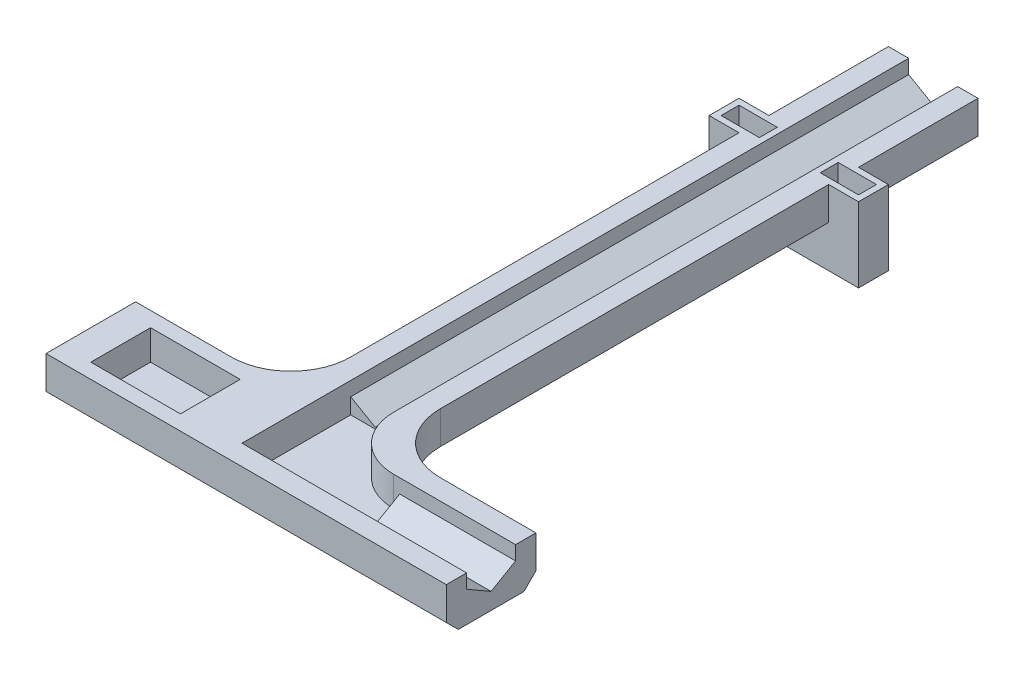
SolidWorks part; units mm, degrees
ref_plane "Front Plane" through (0, 0, 0) normal (0, 0, 1) x (1, 0, 0)
ref_plane "Top Plane" through (0, 0, 0) normal (0, 1, 0) x (1, 0, 0)
ref_plane "Right Plane" through (0, 0, 0) normal (1, 0, 0) x (0, 0, -1)
sketch "Sketch1" plane through (0, 0, 0) normal (0, 1, 0) x (1, 0, 0)
  line L0 (0, 0) -> (0, 15)
  line L1 (0, 15) -> (16, 15)
  line L2 (41, 25) -> (41, 115)
  line L3 (41, 115) -> (26, 115)
  line L4 (26, 115) -> (26, 25)
  line L5 (51, 15) -> (67, 15)
  line L6 (67, 15) -> (67, 0)
  line L7 (67, 0) -> (0, 0)
  arc A0 (26, 25) -> (16, 15) centre (16, 25) cw
  arc A1 (51, 15) -> (41, 25) centre (51, 25) cw
  point P10 (33.5, 115)
  point P11 (33.5, 0)
  point P16 (41, 15)
  dimension "D5" = 10
  dimension "D1" = 15
  dimension "D2" = 67
  dimension "D3" = 100
  dimension "D4" = 15
extrude "Boss-Extrude1" add sketch "Sketch1" along normal blind 7.5 contours L3 L4 L1 L2 | L7 L6 L5 L1 L0
sketch "Sketch2" plane through (0, 7.5, 0) normal (0, 1, 0) x (1, 0, 0)
  line L0 (33.5, 115) -> (33.5, 7.5)
  line L1 (41, 115) -> (26, 115) construction
  line L2 (33.5, 7.5) -> (67, 7.5)
  line L3 (67, 15) -> (67, 0) construction
  point P8 (67, 7.5)
sketch "Sketch3" plane through (0, 0, -115) normal (0, 0, -1) x (-1, 0, 0)
  line L0 (-41, 7.5) -> (-26, 7.5) construction
  line L1 (-37.6, 5.1329) -> (-33.5, 2.7657)
  line L2 (-33.5, 2.7657) -> (-29.4, 5.1329)
  line L3 (-29.4, 5.1329) -> (-29.4, 9.8671)
  line L4 (-29.4, 9.8671) -> (-33.5, 12.2343)
  line L5 (-33.5, 12.2343) -> (-37.6, 9.8671)
  line L6 (-37.6, 9.8671) -> (-37.6, 5.1329)
  circle A0 centre (-33.5, 7.5) radius 4.1 construction
  dimension "D1" = 8.2
sweep "Cut-Sweep1" cut profiles "Sketch3" path "Sketch2"
sketch "Sketch7" plane through (0, 7.5, 0) normal (0, 1, 0) x (1, 0, 0)
  line L5 (47.6, 11.6) -> (47.6, 3.4)
  line L6 (67, 3.4) -> (29.4, 3.4) construction
  line L7 (47.6, 3.4) -> (29.4, 3.4)
  line L8 (29.4, 3.4) -> (29.4, 21.6)
  line L14 (37.6, 115) -> (37.6, 11.6) construction
  line L19 (29.4, 21.6) -> (37.6, 21.6)
  line L20 (29.4, 115) -> (29.4, 3.4) construction
  line L21 (37.6, 115) -> (37.6, 11.6) construction
  line L22 (37.6, 21.6) -> (37.6, 20.6)
  line L23 (46.6, 11.6) -> (47.6, 11.6)
  line L24 (37.6, 11.6) -> (67, 11.6) construction
  arc A0 (37.6, 20.6) -> (46.6, 11.6) centre (46.6, 20.6) ccw
  point P16 (37.6, 11.6)
  dimension "D3" = 9
  dimension "D1" = 10
  dimension "D2" = 10
extrude "Cut-Extrude6" cut sketch "Sketch7" against normal blind 5
sketch "Sketch10" plane through (0, 0, -115) normal (0, 0, -1) x (-1, 0, 0)
  line L0 (-46, 7.5) -> (-21, 7.5)
  line L1 (-46, 7.5) -> (-46, -5)
  line L2 (-21, 7.5) -> (-21, -5)
  line L3 (-46, -5) -> (-21, -5)
  line L4 (-51, 7.5) -> (-67, 7.5) construction
  line L5 (0, 7.5) -> (-16, 7.5) construction
  line L7 (-41, 0) -> (-26, 0) construction
  line L9 (-41, 7.5) -> (-26, 7.5)
  line L10 (-41, 7.5) -> (-41, 0)
  line L11 (-41, 0) -> (-26, 0)
  line L12 (-26, 7.5) -> (-26, 0)
  point P10 (-33.5, 0)
  point P11 (-33.5, -5)
  line M10 (-41, 7.5) -> (-41, 0)
  line M11 (-41, 0) -> (-26, 0)
  line M12 (-26, 0) -> (-26, 7.5)
  dimension "D1" = 25
  dimension "D2" = 12.5
extrude "Boss-Extrude2" add sketch "Sketch10" against normal blind 5 from offset 20 contours L1 L3 L2 L0 M12 M11 M10 offset against normal yes
chamfer "Chamfer1" distance 2 angle 45 9 edges at (33.5, 0, 0) (8, 0, -15) (26, 0, -57.5) (59, 0, -15) (41, 0, -57.5) (26, 0, -105) (41, 0, -105) (23.0711, 0, -17.9289) (43.9289, 0, -17.9289)
sketch "Sketch11" plane through (0, 7.5, 0) normal (0, 1, 0) x (1, 0, 0)
  line L1 (5, 12.5) -> (20, 12.5)
  line L2 (5, 12.5) -> (5, 2.5)
  line L3 (5, 2.5) -> (20, 2.5)
  line L4 (20, 12.5) -> (20, 2.5)
  line L5 (0, 0) -> (0, 15) construction
  line L6 (26, 90) -> (21, 90) construction
  line L7 (22, 94) -> (28.4, 94)
  line L8 (22, 94) -> (22, 91)
  line L9 (22, 91) -> (28.4, 91)
  line L10 (28.4, 94) -> (28.4, 91)
  line L11 (21, 90) -> (21, 95) construction
  line L12 (29.4, 3.4) -> (29.4, 115) construction
  line L13 (33.5, 115) -> (33.5, 0) construction
  line L14 (67, 0) -> (0, 0) construction
  line L15 (38.6, 94) -> (38.6, 91)
  line L16 (45, 91) -> (38.6, 91)
  line L17 (45, 94) -> (45, 91)
  line L18 (45, 94) -> (38.6, 94)
  point P6 (0, 7.5)
  point P7 (5, 7.5)
  point P18 (21, 92.5)
  point P19 (22, 92.5)
  dimension "D1" = 10
  dimension "D2" = 15
  dimension "D3" = 5
  dimension "D4" = 1
  dimension "D5" = 1
  dimension "D6" = 1
extrude "Cut-Extrude7" cut sketch "Sketch11" against normal blind 5
